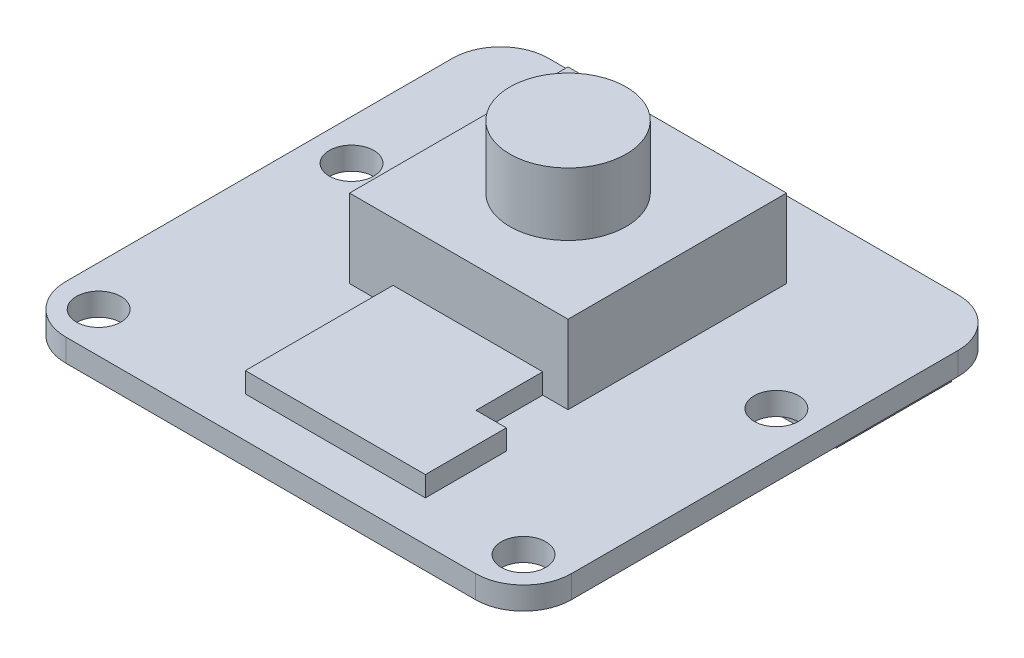
SolidWorks part; units mm, degrees
ref_plane "Front Plane" through (0, 0, 0) normal (0, 0, 1) x (1, 0, 0)
ref_plane "Top Plane" through (0, 0, 0) normal (0, 1, 0) x (1, 0, 0)
ref_plane "Right Plane" through (0, 0, 0) normal (1, 0, 0) x (0, 0, -1)
sketch "Sketch1" plane through (0, 0, 0) normal (0, 1, 0) x (1, 0, 0)
  line L1 (-10.125, 11.931) -> (10.125, 11.931)
  line L2 (-12.5, 9.556) -> (-12.5, -9.556)
  line L3 (-10.125, -11.931) -> (10.125, -11.931)
  line L4 (12.5, 9.556) -> (12.5, -9.556)
  line L5 (-12.5, 11.931) -> (12.5, -11.931) construction
  line L6 (-12.5, -11.931) -> (12.5, 11.931) construction
  arc A0 (-12.5, -9.556) -> (-10.125, -11.931) centre (-10.125, -9.556) ccw
  arc A1 (10.125, -11.931) -> (12.5, -9.556) centre (10.125, -9.556) ccw
  arc A2 (10.125, 11.931) -> (12.5, 9.556) centre (10.125, 9.556) cw
  arc A3 (-10.125, 11.931) -> (-12.5, 9.556) centre (-10.125, 9.556) ccw
  point P0 (0, 0)
  dimension "D3" = 2.375
  dimension "D1" = 25
  dimension "D2" = 23.862
extrude "MainBoard" add sketch "Sketch1" along normal blind 1.12
sketch "Sketch2" plane through (0, 1.12, 0) normal (0, 1, 0) x (1, 0, 0)
  line L0 (-10.125, -11.931) -> (10.125, -11.931) construction
  line L1 (12.5, -9.556) -> (12.5, 9.556) construction
  line L2 (-12.5, 9.556) -> (-12.5, -9.556) construction
  circle A0 centre (-10.5, -9.931) radius 1.1
  circle A1 centre (-10.5, 2.569) radius 1.1
  circle A2 centre (10.5, -9.931) radius 1.1
  circle A3 centre (10.5, 2.569) radius 1.1
  dimension "D1" = 2.2
  dimension "D2" = 2
  dimension "D3" = 2
  dimension "D5" = 2
  dimension "D4" = 14.5
extrude "BoardHoles" cut sketch "Sketch2" against normal up to surface (1.12 mm away) up to face at (0, 0, 0)
sketch "CamBod" plane through (0, 1.12, 0) normal (0, 1, 0) x (1, 0, 0)
  line L0 (-10.125, -11.931) -> (10.125, -11.931) construction
  line L1 (-5.4, 8.169) -> (5.4, 8.169)
  line L2 (-5.4, 8.169) -> (-5.4, -2.631)
  line L3 (-5.4, -2.631) -> (5.4, -2.631)
  line L4 (5.4, 8.169) -> (5.4, -2.631)
  line L5 (-5.4, 8.169) -> (5.4, -2.631) construction
  line L6 (-5.4, -2.631) -> (5.4, 8.169) construction
  line L7 (0, 11.931) -> (0, -11.931) construction
  line L8 (10.125, 11.931) -> (-10.125, 11.931) construction
  circle A0 centre (-10.5, -9.931) radius 1.1 construction
  point P0 (0, 2.769)
  dimension "D1" = 10.8
  dimension "D2" = 10.8
  dimension "D3" = 7.3
extrude "Cam Base" add sketch "CamBod" along normal blind 3.875
sketch "Sketch4" plane through (0, 4.995, 0) normal (0, 1, 0) x (1, 0, 0)
  line L0 (-5.4, 8.169) -> (5.4, -2.631) construction
  line L1 (-5.4, -2.631) -> (5.4, 8.169) construction
  line L2 (0, 8.169) -> (0, -2.631) construction
  line L3 (5.4, 8.169) -> (-5.4, 8.169) construction
  line L4 (-5.4, -2.631) -> (5.4, -2.631) construction
  circle A0 centre (0, 2.769) radius 2.875
  dimension "D1" = 5.75
extrude "CamLens" add sketch "Sketch4" along normal blind 6.98 from surface at -3.875 starting at face at (-10.5, 1.12, -1.469)
sketch "Sketch5" plane through (0, 0, 0) normal (0, -1, 0) x (1, 0, 0)
  line L0 (0, 11.931) -> (0, -11.931) construction
  line L1 (-10.125, 11.931) -> (10.125, 11.931) construction
  line L2 (10.125, -11.931) -> (-10.125, -11.931) construction
  line L4 (-9.805, -11.931) -> (9.805, -11.931)
  line L5 (-9.805, -11.931) -> (-9.805, -6.221)
  line L6 (-9.805, -6.221) -> (9.805, -6.221)
  line L7 (9.805, -11.931) -> (9.805, -6.221)
  line L8 (-9.805, -11.931) -> (9.805, -6.221) construction
  line L9 (-9.805, -6.221) -> (9.805, -11.931) construction
  point P6 (0, -9.076)
  dimension "D1" = 19.61
  dimension "D2" = 5.71
extrude "Ribbon Port" add sketch "Sketch5" along normal blind 2.75
sketch "Sketch6" plane through (0, 1.12, 0) normal (0, 1, 0) x (1, 0, 0)
  line L0 (-3.25, -9.931) -> (-3.25, -2.631)
  line L1 (-3.25, -9.931) -> (5.65, -9.931)
  line L3 (4.15, -5.931) -> (5.65, -5.931)
  line L4 (5.65, -9.931) -> (5.65, -5.931)
  line L6 (4.15, -5.931) -> (4.15, -2.631)
  line L7 (-5.4, -2.631) -> (5.4, -2.631) construction
  line L8 (5.4, -2.631) -> (5.4, 8.169) construction
  line L9 (5.4, -2.631) -> (5.4, 8.169) construction
  line L10 (-3.25, -2.631) -> (4.15, -2.631)
  dimension "D1" = 8.9
  dimension "D2" = 4
  dimension "D3" = 3.3
  dimension "D4" = 0.25
  dimension "D5" = 1.25
extrude "Little Module" add sketch "Sketch6" along normal blind 1
equation "\"HoleSize\"= 2.2mm"
equation "\"D1@Sketch2\"=\"HoleSize\""
